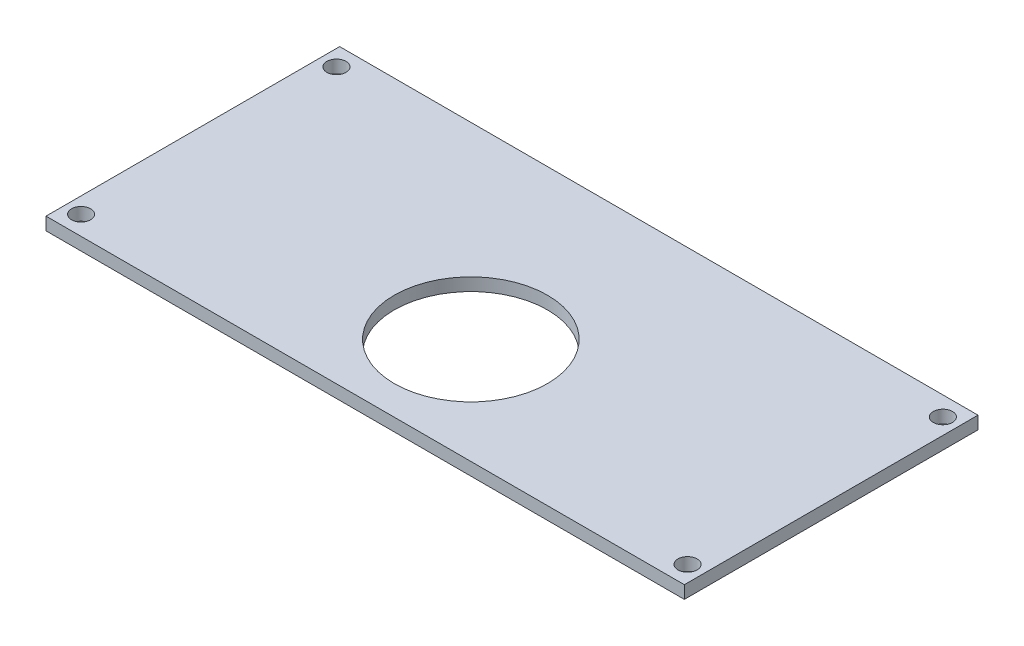
SolidWorks part; units mm, degrees
ref_plane "前视基准面" through (0, 0, 0) normal (0, 0, 1) x (1, 0, 0)
ref_plane "上视基准面" through (0, 0, 0) normal (0, 1, 0) x (1, 0, 0)
ref_plane "右视基准面" through (0, 0, 0) normal (1, 0, 0) x (0, 0, -1)
other "Configuration Table"
sketch "草图1" plane through (0, 0, 0) normal (0, 1, 0) x (1, 0, 0)
  line L0 (50, 46) -> (50, 0) construction
  line L1 (0, 0) -> (100, 0)
  line L2 (0, 0) -> (0, 46)
  line L3 (0, 46) -> (100, 46)
  line L4 (100, 0) -> (100, 46)
  line L5 (0, 23) -> (100, 23) construction
  circle A0 centre (2.5, 43) radius 1.5
  circle A4 centre (2.5, 3) radius 1.5
  circle A5 centre (97.5, 3) radius 1.5
  circle A6 centre (97.5, 43) radius 1.5
  circle A7 centre (50, 16.5563) radius 12
  point P7 (0, 0)
  point P20 (0, 0)
  dimension "D3" = 3
  dimension "D4" = 40
  dimension "D6" = 24
  dimension "D1" = 100
  dimension "D2" = 46
  dimension "D5" = 95
extrude "凸台-拉伸1" add sketch "草图1" along normal blind 2
